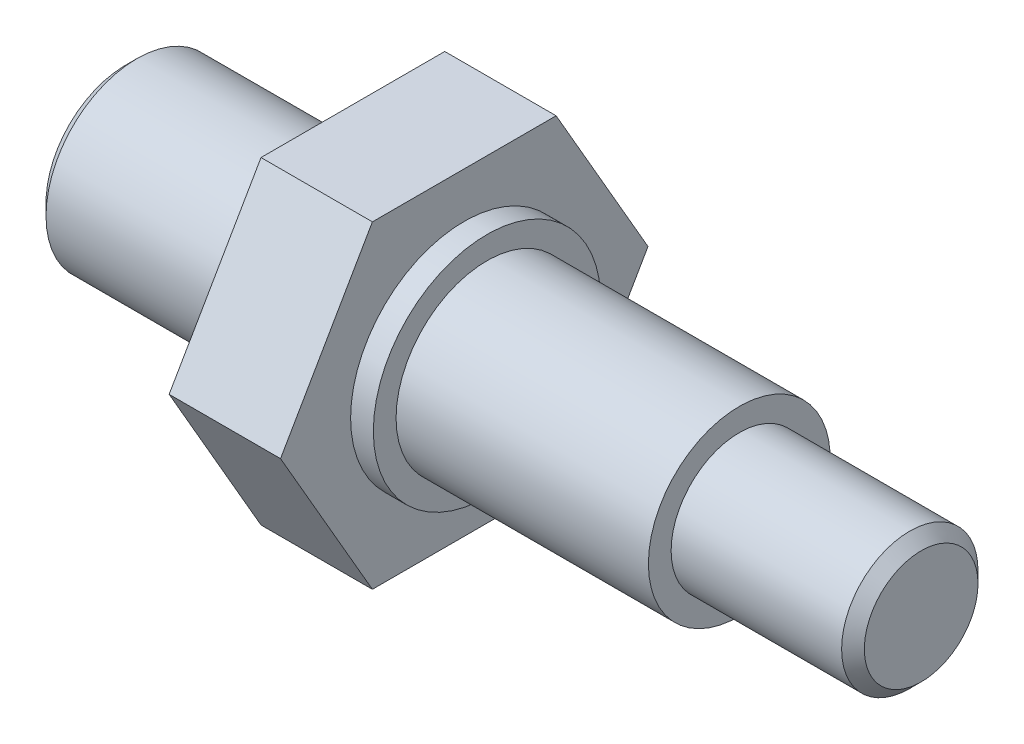
SolidWorks part; units mm, degrees
ref_plane "Front" through (0, 0, 0) normal (0, 0, 1) x (1, 0, 0)
ref_plane "Top" through (0, 0, 0) normal (0, 1, 0) x (1, 0, 0)
ref_plane "Right" through (0, 0, 0) normal (1, 0, 0) x (0, 0, -1)
sketch "Sketch1" plane through (0, 0, 0) normal (1, 0, 0) x (0, 0, -1)
  line L1 (-8.0829, 0) -> (-4.0415, -7)
  line L2 (-4.0415, -7) -> (4.0414, -7)
  line L3 (4.0414, -7) -> (8.0829, 0)
  line L4 (8.0829, 0) -> (4.0415, 7)
  line L5 (4.0415, 7) -> (-4.0415, 7)
  line L6 (-4.0415, 7) -> (-8.0829, 0)
  circle A0 centre (0, 0) radius 7 construction
  dimension "D1" = 14
extrude "Boss-Extrude1" add sketch "Sketch1" along normal blind 35 from offset 10 offset against normal yes
sketch "Sketch2" plane through (0, 0, 0) normal (0, 1, 0) x (1, 0, 0)
  line L0 (-12.6277, 0) -> (30.8198, 0) construction
  line L1 (0, 8.0829) -> (-10, 8.0829)
  line L3 (-10, 8.0829) -> (-10, 4)
  line L4 (-10, -4.0415) -> (-10, 4.0414) construction
  line L5 (-10, 4) -> (-1, 4)
  line L6 (-1, 4) -> (-1, 3.45)
  line L7 (-1, 3.45) -> (0, 3.45)
  line L8 (0, 3.45) -> (0, 8.0829)
  dimension "D1" = 8
  dimension "D2" = 6.9
  dimension "D3" = 1
revolve "Cut-Revolve1" cut sketch "Sketch2" angle 360 about L0
cosmetic thread "Cosmetic Thread1" parameters "D2"=6.619
sketch "Sketch3" plane through (0, 0, 0) normal (0, 1, 0) x (1, 0, 0)
  line L0 (-14.2462, 0) -> (26.9511, 0) construction
  line L1 (25, 8.0829) -> (25, 3)
  line L3 (17, 3) -> (25, 3)
  line L4 (17, 3) -> (17, 4)
  line L5 (17, 4) -> (5.9, 4)
  line L6 (5.9, 4) -> (5.9, 5)
  line L7 (5.9, 5) -> (4.9, 5)
  line L8 (0, 4.0415) -> (0, 8.0829) construction
  line L9 (4.9, 5) -> (4.9, 8.0829)
  line L10 (4.9, 8.0829) -> (25, 8.0829)
  line L11 (0, -4.0415) -> (0, -8.0829) construction
  line L13 (25, -4.0415) -> (25, 4.0414) construction
  dimension "D1" = 5.9
  dimension "D2" = 17
  dimension "D3" = 6
  dimension "D4" = 8
  dimension "D5" = 10
  dimension "D7" = 4.9
revolve "Cut-Revolve2" cut sketch "Sketch3" angle 360 about L0
cosmetic thread "Cosmetic Thread2" parameters "D1"=6.5, "D2"=4.891
chamfer "Chamfer1" distance 0.5 2 edges at (25, 0, 3) (-10, 0, 4)
